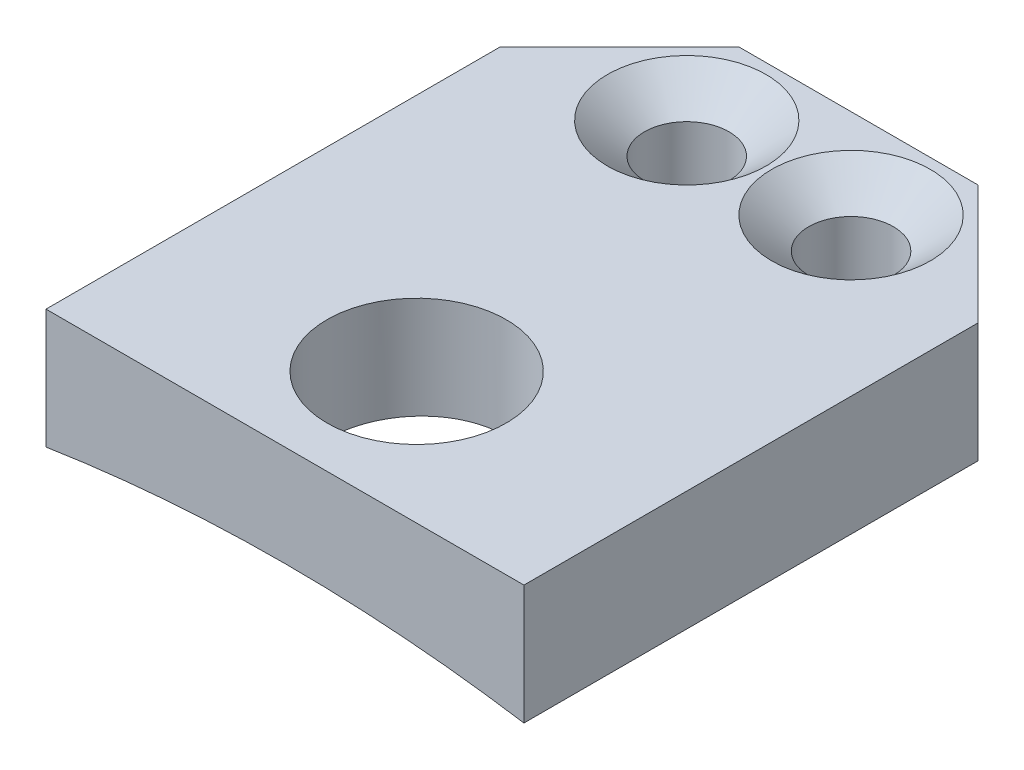
SolidWorks part; units mm, degrees
ref_plane "Front Plane" through (0, 0, 0) normal (0, 0, 1) x (1, 0, 0)
ref_plane "Top Plane" through (0, 0, 0) normal (0, 1, 0) x (1, 0, 0)
ref_plane "Right Plane" through (0, 0, 0) normal (1, 0, 0) x (0, 0, -1)
sketch "Sketch1" plane through (0, 0, 0) normal (0, 1, 0) x (1, 0, 0)
  line L0 (-28.5118, 11.5753) -> (-22.1618, 17.9253)
  line L1 (-22.1618, 17.9253) -> (-9.4618, 17.9253)
  line L2 (-28.5118, 11.5753) -> (-28.5118, -12.5547)
  line L3 (-28.5118, -12.5547) -> (-3.1118, -12.5547)
  line L4 (-3.1118, 11.5753) -> (-3.1118, -12.5547)
  line L5 (-9.4618, 17.9253) -> (-3.1118, 11.5753)
  line L6 (-15.8118, -12.5547) -> (-15.8118, 17.9253) construction
  line L8 (-3.1118, 11.5753) -> (-3.1118, 17.9253) construction
  line L9 (-3.1118, 17.9253) -> (-9.4618, 17.9253) construction
  dimension "D1" = 12.7
  dimension "D2" = 30.48
  dimension "D3" = 25.4
extrude "Boss-Extrude1" add sketch "Sketch1" along normal blind 6.35
sketch "Sketch2" plane through (0, 0, 12.5547) normal (0, 0, 1) x (1, 0, 0)
  circle A0 centre (-15.8118, -81.0531) radius 82.042
  dimension "D1" = 164.084
hole_wizard "CSK for #8 Flat Head Machine Screw (100)1" positions "Sketch3" profile "Sketch4" countersink size "#8" standard "ANSI Inch" end condition through all
sketch "Sketch3" plane through (0, 6.35, 0) normal (0, 1, 0) x (1, 0, 0)
  line L0 (-15.8118, 17.9253) -> (-15.8118, 3.4006) construction
  line L1 (-9.4618, 17.9253) -> (-22.1618, 17.9253) construction
  point P0 (-20.1775, 13.1628)
  point P12 (-11.4462, 13.1628)
  dimension "D1" = 4.7625
  dimension "D2" = 4.3656
sketch "Sketch4" plane through (-20.1775, 6.35, -13.1628) normal (1, 0, 0) x (0, 0, 1)
  line L0 (0, 0) -> (0, 6.35)
  line L1 (0, 6.35) -> (2.2479, 6.35)
  line L2 (2.2479, 6.35) -> (2.2479, 1.6518)
  line L3 (2.2479, 1.6518) -> (4.2164, 0)
  line L5 (4.2164, 0) -> (0, 0)
  line L6 (-2.2479, 1.6518) -> (-4.2164, 0) construction
  line L11 (0, -6.35) -> (0, 107.95) construction
  dimension "Thru Hole Dia." = 4.4958
  dimension "Thru Hole Depth" = 6.35
  dimension "Near C'Sink Dia." = 8.4328
  dimension "Near C'Sink Angle" = 100
extrude "Cut-Extrude1" cut sketch "Sketch2" against normal through all
sketch "Sketch5" plane through (0, 6.35, 0) normal (0, 1, 0) x (1, 0, 0)
  line L1 (-28.5118, 11.5753) -> (-28.5118, -12.5547) construction
  line L2 (-9.4618, 17.9253) -> (-22.1618, 17.9253) construction
  circle A0 centre (-15.7994, -5.5697) radius 1.1303
  dimension "D3" = 2.2606
  dimension "D4" = 12.7124
  dimension "D5" = 23.495
extrude "Cut-Extrude2" cut sketch "Sketch5" against normal through all
sketch "Sketch6" plane through (0, 6.35, 0) normal (0, 1, 0) x (1, 0, 0)
  circle A0 centre (-15.7994, -5.5697) radius 4.7625
  dimension "D1" = 9.525
extrude "Cut-Extrude3" cut sketch "Sketch6" against normal through all
